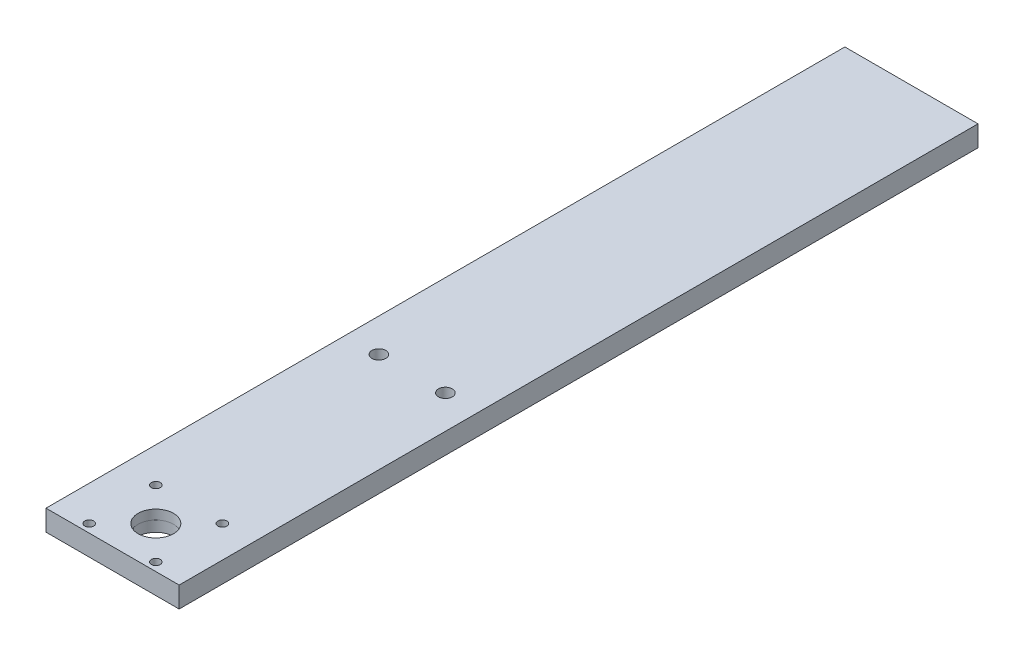
SolidWorks part; units mm, degrees
ref_plane "Front Plane" through (0, 0, 0) normal (0, 0, 1) x (1, 0, 0)
ref_plane "Top Plane" through (0, 0, 0) normal (0, 1, 0) x (1, 0, 0)
ref_plane "Right Plane" through (0, 0, 0) normal (1, 0, 0) x (0, 0, -1)
sketch "Sketch1" plane through (0, 0, 0) normal (0, 0, 1) x (1, 0, 0)
  line L0 (0, 3.9688) -> (0, -3.9688)
  line L1 (-25.4, 0) -> (25.4, 0) construction
  point P6 (0, 0)
  dimension "Width" = 50.8
  dimension "Thk" = 7.9375
sketch "Sketch2" plane through (0, 0, 0) normal (1, 0, 0) x (0, 0, -1)
  line L0 (76.2, 0) -> (-76.2, 0)
  point P4 (0, 0)
  dimension "Length" = 152.4
sketch "Sketch3" plane through (0, 0, 0) normal (0, 0, 1) x (1, 0, 0)
  line L1 (25.4, 3.9688) -> (-25.4, 3.9688)
  line L2 (25.4, 3.9688) -> (25.4, -3.9688)
  line L3 (25.4, -3.9688) -> (-25.4, -3.9688)
  line L4 (-25.4, 3.9688) -> (-25.4, -3.9688)
  line L5 (25.4, 3.9688) -> (-25.4, -3.9688) construction
  line L6 (25.4, -3.9688) -> (-25.4, 3.9688) construction
  point P0 (0, 0)
extrude "Boss-Extrude1" add sketch "Sketch3" along normal up to vertex (76.2 mm away) and the other way up to vertex (76.2 mm away) up to point (0, 0, 76.2) other way up to point (0, 0, -76.2)
sketch "Sketch4" plane through (0, 3.9688, 0) normal (0, 1, 0) x (1, 0, 0)
  point P0 (0.6258, -60.325)
hole_wizard "M12 Clearance Hole2" positions "Sketch5" profile "Sketch7" hole size "M12" standard "ANSI Metric" end condition through all
sketch "Sketch5" plane through (0, 3.9688, 0) normal (0, 1, 0) x (1, 0, 0)
  point P0 (0.6258, -60.325)
sketch "Sketch7" plane through (0.6258, 3.9688, 60.325) normal (1, 0, 0) x (0, 0, 1)
  line L0 (0, 0) -> (0, 7.9375)
  line L1 (0, 7.9375) -> (6.75, 7.9375)
  line L2 (6.75, 7.9375) -> (6.75, 0)
  line L5 (6.75, 0) -> (0, 0)
  line L11 (0, -6.35) -> (0, 107.95) construction
  dimension "Thru Hole Dia." = 13.5
  dimension "Thru Hole Depth" = 7.9375
sketch "Sketch8" plane through (0, 3.9688, 0) normal (0, 1, 0) x (1, 0, 0)
  point P1 (0.6258, -38.1)
hole_wizard "M12 Clearance Hole1" [suppressed] positions "Sketch9" profile "Sketch10" hole size "M12" standard "ANSI Metric"
sketch "Sketch9" plane through (0, 3.9688, 0) normal (0, 1, 0) x (1, 0, 0)
  point P5 (0.6258, -38.1)
sketch "Sketch10" plane through (0.6258, 3.9688, 38.1) normal (1, 0, 0) x (0, 0, 1)
  line L0 (0, 0) -> (0, 7.9375)
  line L1 (0, 7.9375) -> (6.75, 7.9375)
  line L2 (6.75, 7.9375) -> (6.75, 0)
  line L5 (6.75, 0) -> (0, 0)
  line L11 (0, -6.35) -> (0, 107.95) construction
  dimension "Thru Hole Dia." = 13.5
  dimension "Thru Hole Depth" = 7.9375
sketch "Sketch11" plane through (0, 3.9688, 0) normal (0, 1, 0) x (1, 0, 0)
  circle A0 centre (0.6258, -38.1) radius 7.25
  dimension "D1" = 14.5
extrude "Cut-Extrude1" [suppressed] cut sketch "Sketch11" against normal blind 4.5 contours A0
sketch "Sketch12" plane through (0, -3.9688, 0) normal (0, 1, 0) x (1, 0, 0)
  line L0 (-12.7, 38.1) -> (12.7, 38.1) construction
  line L1 (25.4, 76.2) -> (-25.4, 76.2) construction
  point P2 (0, 38.1)
  point P5 (0, 76.2)
  point P7 (12.7, 38.1)
  point P8 (-12.7, 38.1)
  dimension "D1" = 25.4
  dimension "D2" = 38.1
hole_wizard "CSK for M5 Flat Head Machine Screw1" positions "Sketch15" profile "Sketch17" countersink size "M5" standard "ANSI Metric" end condition up to next
sketch "Sketch15" plane through (0, -3.9688, 0) normal (0, -1, 0) x (-1, 0, 0)
  point P0 (-12.7, 38.1)
  point P3 (12.7, 38.1)
sketch "Sketch17" plane through (12.7, -3.9688, -38.1) normal (1, 0, 0) x (0, 0, -1)
  line L0 (0, 0) -> (0, 7.9375)
  line L1 (0, 7.9375) -> (2.65, 7.9375)
  line L2 (2.65, 7.9375) -> (2.65, 2.55)
  line L3 (2.65, 2.55) -> (5.2, 0)
  line L5 (5.2, 0) -> (0, 0)
  line L6 (-2.65, 2.55) -> (-5.2, 0) construction
  line L11 (0, -6.35) -> (0, 107.95) construction
  dimension "Thru Hole Dia." = 5.3
  dimension "Thru Hole Depth" = 7.9375
  dimension "Near C'Sink Dia." = 10.4
  dimension "Near C'Sink Angle" = 90
ref_plane "Plane1" through (25.4, 3.9688, -76.2) normal (-1, 0, 0) x (0, 0, 1)
sketch "Sketch19" plane through (0, 3.9688, 0) normal (0, 1, 0) x (1, 0, 0)
  line L0 (12.7, 60.325) -> (-12.7, 60.325) construction
  line L1 (25.4, 76.2) -> (-25.4, 76.2) construction
  point P4 (0, 60.325)
  point P5 (0, 76.2)
  point P7 (-12.7, 60.325)
  point P8 (12.7, 60.325)
  dimension "D1" = 15.875
  dimension "D2" = 25.4
hole_wizard "CSK for M5 Flat Head Machine Screw2" [suppressed] positions "Sketch20" profile "Sketch21" countersink size "M5" standard "ANSI Metric"
sketch "Sketch20" plane through (0, 3.9688, 0) normal (0, 1, 0) x (1, 0, 0)
  point P0 (12.7, 60.325)
  point P3 (-12.7, 60.325)
sketch "Sketch21" plane through (12.7, 3.9688, -60.325) normal (1, 0, 0) x (0, 0, 1)
  line L0 (0, 0) -> (0, 7.9375)
  line L1 (0, 7.9375) -> (2.65, 7.9375)
  line L2 (2.65, 7.9375) -> (2.65, 2.55)
  line L3 (2.65, 2.55) -> (5.2, 0)
  line L5 (5.2, 0) -> (0, 0)
  line L6 (-2.65, 2.55) -> (-5.2, 0) construction
  line L11 (0, -6.35) -> (0, 107.95) construction
  dimension "Thru Hole Dia." = 5.3
  dimension "Thru Hole Depth" = 7.9375
  dimension "Near C'Sink Dia." = 10.4
  dimension "Near C'Sink Angle" = 90
sketch "Sketch22" [suppressed] plane through (0, 3.9688, 0) normal (0, 1, 0) x (1, 0, 0)
  point P0 (-12.7, -73.025)
  point P1 (12.7, -73.025)
  point P2 (12.7, -3.175)
  point P4 (-12.7, -3.175)
hole_wizard "CSK for M3 Flat Head Machine Screw1" [suppressed] positions "Sketch23" profile "Sketch25" countersink size "M3" standard "ANSI Metric"
sketch "Sketch23" [suppressed] plane through (0, 3.9688, 0) normal (0, 1, 0) x (1, 0, 0)
  point P0 (-12.7, -73.025)
  point P3 (12.7, -73.025)
  point P6 (12.7, -3.175)
  point P9 (-12.7, -3.175)
sketch "Sketch25" plane through (-12.7, 3.9688, 73.025) normal (1, 0, 0) x (0, 0, 1)
  line L0 (0, 0) -> (0, 7.9375)
  line L1 (0, 7.9375) -> (1.7, 7.9375)
  line L2 (1.7, 7.9375) -> (1.7, 1.45)
  line L3 (1.7, 1.45) -> (3.15, 0)
  line L5 (3.15, 0) -> (0, 0)
  line L6 (-1.7, 1.45) -> (-3.15, 0) construction
  line L11 (0, -6.35) -> (0, 107.95) construction
  dimension "Thru Hole Dia." = 3.4
  dimension "Thru Hole Depth" = 7.9375
  dimension "Near C'Sink Dia." = 6.3
  dimension "Near C'Sink Angle" = 90
sketch "Sketch26" plane through (0, 3.9688, 0) normal (0, 1, 0) x (1, 0, 0)
  line L0 (-25.4, -76.2) -> (-25.4, 76.2) construction
  line L1 (25.4, 76.2) -> (-25.4, 76.2)
  line L2 (25.4, 76.2) -> (25.4, 228.6)
  line L3 (25.4, 228.6) -> (-25.4, 228.6)
  line L4 (-25.4, 76.2) -> (-25.4, 228.6)
  dimension "D1" = 152.4
extrude "Boss-Extrude2" add sketch "Sketch26" against normal up to surface (7.9375 mm away) up to face at (-12.7, -3.9688, -43.3)
sketch "Sketch27" plane through (0, -3.9688, 0) normal (0, -1, 0) x (1, 0, 0)
  circle A0 centre (0.6258, 60.325) radius 7.112
  dimension "D1" = 14.224
extrude "Cut-Extrude2" cut sketch "Sketch27" against normal blind 4.318
sketch "Sketch29" plane through (0, -3.9688, 0) normal (0, -1, 0) x (1, 0, 0)
  line L1 (-12.0742, 73.025) -> (13.3258, 73.025)
  line L2 (-12.0742, 73.025) -> (-12.0742, 47.625)
  line L3 (-12.0742, 47.625) -> (13.3258, 47.625)
  line L4 (13.3258, 73.025) -> (13.3258, 47.625)
  line L5 (-12.0742, 73.025) -> (13.3258, 47.625) construction
  line L6 (-12.0742, 47.625) -> (13.3258, 73.025) construction
  point P0 (0.6258, 60.325)
  dimension "D1" = 25.4
  dimension "D2" = 25.4
hole_wizard "M3 Clearance Hole1" positions "Sketch30" profile "Sketch32" hole size "M3" standard "ANSI Metric"
sketch "Sketch30" plane through (0, -3.9688, 0) normal (0, -1, 0) x (-1, 0, 0)
  point P0 (-13.3258, -47.625)
  point P3 (-13.3258, -73.025)
  point P6 (12.0742, -73.025)
  point P9 (12.0742, -47.625)
sketch "Sketch32" plane through (13.3258, -3.9688, 47.625) normal (1, 0, 0) x (0, 0, -1)
  line L0 (0, 0) -> (0, 16.2615)
  line L1 (0, 16.2615) -> (1.7, 15.24)
  line L2 (1.7, 15.24) -> (1.7, 0)
  line L5 (1.7, 0) -> (0, 0)
  line L10 (0, 16.2615) -> (-1.7, 15.24) construction
  line L11 (0, -6.35) -> (0, 107.95) construction
  dimension "Hole Dia." = 3.4
  dimension "Hole Depth" = 15.24
  dimension "Drill Angle" = 118
